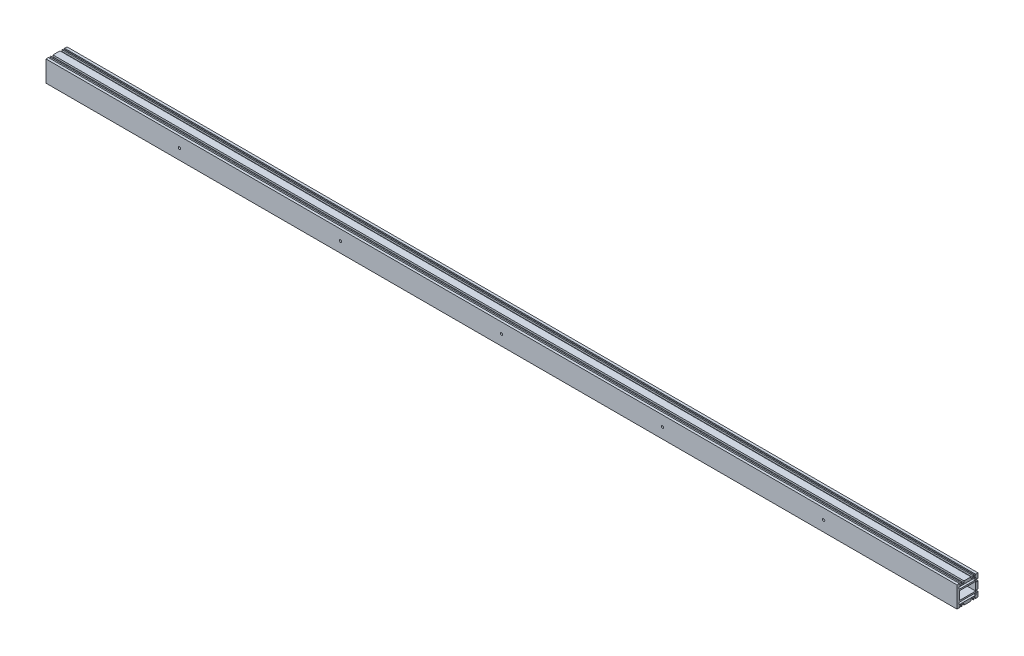
SolidWorks part; units mm, degrees
ref_plane "前视基准面" through (0, 0, 0) normal (0, 0, 1) x (1, 0, 0)
ref_plane "上视基准面" through (0, 0, 0) normal (0, 1, 0) x (1, 0, 0)
ref_plane "右视基准面" through (0, 0, 0) normal (1, 0, 0) x (0, 0, -1)
sketch "草图1" plane through (0, 0, 0) normal (1, 0, 0) x (0, 0, -1)
  line L0 (-15, 15) -> (15, -15) construction
  line L1 (-15, 15) -> (-11.5, 15)
  line L2 (-15, 15) -> (-15, -15)
  line L3 (-15, -15) -> (-11.5, -15)
  line L4 (15, 15) -> (15, 8)
  line L5 (15, 15) -> (-15, -15) construction
  line L6 (-11.5, 15) -> (-11.5, 13.5)
  line L7 (-11.5, 13.5) -> (-11, 13.5)
  line L8 (-11, 13.5) -> (-11, 12)
  line L9 (-11, 12) -> (-9.5, 12)
  line L10 (-9.5, 12) -> (-9.5, 15)
  line L11 (-9.5, 15) -> (-8, 15)
  line L12 (-8, 15) -> (-8, 12.5)
  line L13 (-8, 12.5) -> (-5, 12.5)
  line L14 (-5, 12.5) -> (-5, 15)
  line L15 (-5, 15) -> (5, 15)
  line L16 (0, 21.5201) -> (0, -18.309) construction
  line L17 (0, 55) -> (0, -55) construction
  line L18 (5, 12.5) -> (5, 15)
  line L19 (8, 12.5) -> (5, 12.5)
  line L20 (8, 15) -> (8, 12.5)
  line L21 (9.5, 15) -> (8, 15)
  line L22 (9.5, 12) -> (9.5, 15)
  line L23 (11, 12) -> (9.5, 12)
  line L24 (11, 13.5) -> (11, 12)
  line L25 (11.5, 13.5) -> (11, 13.5)
  line L26 (11.5, 15) -> (11.5, 13.5)
  line L27 (8, 15) -> (9.5, 15)
  line L28 (11.5, 15) -> (15, 15)
  line L29 (-19.8303, 0) -> (22.13, 0) construction
  line L30 (55, 0) -> (-55, 0) construction
  line L31 (8, -15) -> (9.5, -15)
  line L32 (11.5, -15) -> (11.5, -13.5)
  line L33 (11.5, -13.5) -> (11, -13.5)
  line L34 (11, -13.5) -> (11, -12)
  line L35 (11, -12) -> (9.5, -12)
  line L36 (9.5, -12) -> (9.5, -15)
  line L37 (9.5, -15) -> (8, -15)
  line L38 (8, -15) -> (8, -12.5)
  line L39 (8, -12.5) -> (5, -12.5)
  line L40 (5, -12.5) -> (5, -15)
  line L41 (-5, -15) -> (5, -15)
  line L42 (-5, -12.5) -> (-5, -15)
  line L43 (-8, -12.5) -> (-5, -12.5)
  line L44 (-8, -15) -> (-8, -12.5)
  line L45 (-9.5, -15) -> (-8, -15)
  line L46 (-9.5, -12) -> (-9.5, -15)
  line L47 (-11, -12) -> (-9.5, -12)
  line L48 (-11, -13.5) -> (-11, -12)
  line L49 (-11.5, -13.5) -> (-11, -13.5)
  line L50 (-11.5, -15) -> (-11.5, -13.5)
  line L51 (-9.5, -15) -> (-8, -15)
  line L52 (-5, -15) -> (5, -15)
  line L53 (8, -15) -> (9.5, -15)
  line L54 (11.5, -15) -> (15, -15)
  line L55 (15, 8) -> (12.5, 8)
  line L56 (12.5, 8) -> (12.5, 5)
  line L57 (12.5, 5) -> (15, 5)
  line L58 (12.5, -5) -> (15, -5)
  line L59 (12.5, -8) -> (12.5, -5)
  line L60 (15, -8) -> (12.5, -8)
  line L61 (15, 5) -> (15, -5)
  line L62 (15, -8) -> (15, -15)
  line L63 (12, -10.5) -> (12, -8.5)
  line L64 (-11.5, 11) -> (11.5, 11)
  line L65 (-12, 10.5) -> (-12, 8.5)
  line L66 (-11.5, 8) -> (11.5, 8)
  line L67 (12, 10.5) -> (12, 8.5)
  line L68 (-11.5, -8) -> (11.5, -8)
  line L69 (-12, -10.5) -> (-12, -8.5)
  line L70 (-11.5, -11) -> (11.5, -11)
  line L72 (-11.75, 6) -> (11.75, 6)
  line L73 (-11.75, 6) -> (-11.75, -6)
  line L74 (-11.75, -6) -> (11.75, -6)
  line L75 (11.75, 6) -> (11.75, -6)
  arc A0 (12, 8.5) -> (11.5, 8) centre (11.5, 8.5) cw
  arc A1 (11.5, 11) -> (12, 10.5) centre (11.5, 10.5) cw
  arc A2 (-11.5, 11) -> (-12, 10.5) centre (-11.5, 10.5) ccw
  arc A3 (-11.5, 8) -> (-12, 8.5) centre (-11.5, 8.5) cw
  arc A8 (-11.5, -8) -> (-12, -8.5) centre (-11.5, -8.5) ccw
  arc A9 (-11.5, -11) -> (-12, -10.5) centre (-11.5, -10.5) cw
  arc A10 (11.5, -11) -> (12, -10.5) centre (11.5, -10.5) ccw
  arc A11 (12, -8.5) -> (11.5, -8) centre (11.5, -8.5) ccw
  point P69 (12, 11)
  point P72 (-12, 11)
  point P77 (-11, -13.5)
  point P80 (11, -13.5)
  point P83 (11, 13.5)
  point P86 (-11, 13.5)
  point P99 (-12, -11)
  point P100 (12, -11)
  dimension "D17" = 0.5
  dimension "D1" = 3.5
  dimension "D2" = 1.5
  dimension "D3" = 0.5
  dimension "D4" = 1.5
  dimension "D5" = 3
  dimension "D6" = 30
  dimension "D7" = 30
  dimension "D8" = 1.5
  dimension "D9" = 2.5
  dimension "D10" = 3
  dimension "D11" = 2.5
  dimension "D12" = 7
  dimension "D13" = 3
  dimension "D14" = 4
  dimension "D15" = 3
  dimension "D16" = 24
  dimension "D19" = 23.5
  dimension "D20" = 12
extrude "凸台-拉伸1" add sketch "草图1" along normal mid plane 1301
hole_wizard "M6 螺纹孔1" positions "草图3" profile "草图2" tap size "M6" standard "GB"
sketch "草图3" plane through (0, 0, -15) normal (0, 0, -1) x (-1, 0, 0)
  point P0 (-630.5, 0)
  point P3 (-615.5, 0)
  point P6 (342.5, 0)
  point P9 (327.5, 0)
  point P12 (427.5, 0)
  point P15 (412.5, 0)
  point P18 (630.5, 0)
  point P21 (615.5, 0)
sketch "草图2" plane through (630.5, 0, -15) normal (1, 0, 0) x (0, 1, 0)
  line L0 (0, 0) -> (0, 20.5022)
  line L1 (0, 20.5022) -> (2.5, 19)
  line L2 (2.5, 19) -> (2.5, 0)
  line L5 (2.5, 0) -> (0, 0)
  line L10 (0, 20.5022) -> (-2.5, 19) construction
  line L11 (0, -6.35) -> (0, 107.95) construction
  dimension "螺纹孔钻头直径" = 5
  dimension "螺纹孔钻头深度" = 19
  dimension "导头角度" = 118
cosmetic thread "孔螺蚊线1" parameters "D1"=3.25, "D2"=6
cosmetic thread "孔螺蚊线2" parameters "D1"=3.25, "D2"=6
cosmetic thread "孔螺蚊线3" parameters "D1"=3.25, "D2"=6
cosmetic thread "孔螺蚊线4" parameters "D1"=3.25, "D2"=6
cosmetic thread "孔螺蚊线7" parameters "D1"=3.25, "D2"=6
cosmetic thread "孔螺蚊线8" parameters "D1"=3.25, "D2"=6
cosmetic thread "孔螺蚊线9" parameters "D1"=3.25, "D2"=6
cosmetic thread "孔螺蚊线10" parameters "D1"=3.25, "D2"=6
hole_wizard "M4 螺纹孔1" positions "草图5" profile "草图4" tap size "M4" standard "GB"
sketch "草图5" plane through (0, 0, 15) normal (0, 0, 1) x (1, 0, 0)
  line L0 (650.5, -15) -> (-650.5, -15) construction
  line L1 (650.5, 15) -> (650.5, -15) construction
  line L2 (-650.5, 15) -> (-650.5, -15) construction
  point P0 (-460, 0)
  point P2 (-230, 0)
  point P4 (0, 0)
  point P7 (230, 0)
  point P9 (460, 0)
  dimension "D1" = 15
  dimension "D2" = 190.5
  dimension "D3" = 420.5
  dimension "D4" = 15
  dimension "D5" = 15
  dimension "D6" = 190.5
  dimension "D7" = 420.5
  dimension "D8" = 15
sketch "草图4" plane through (-460, 0, 15) normal (1, 0, 0) x (0, -1, 0)
  line L0 (0, 0) -> (0, 16.4914)
  line L1 (0, 16.4914) -> (1.65, 15.5)
  line L2 (1.65, 15.5) -> (1.65, 0)
  line L5 (1.65, 0) -> (0, 0)
  line L10 (0, 16.4914) -> (-1.65, 15.5) construction
  line L11 (0, -6.35) -> (0, 107.95) construction
  dimension "螺纹孔钻头直径" = 3.3
  dimension "螺纹孔钻头深度" = 15.5
  dimension "导头角度" = 118
cosmetic thread "孔螺蚊线11" parameters "D1"=3.25, "D2"=4
cosmetic thread "孔螺蚊线12" parameters "D1"=3.25, "D2"=4
cosmetic thread "孔螺蚊线13" parameters "D1"=3.25, "D2"=4
cosmetic thread "孔螺蚊线14" parameters "D1"=3.25, "D2"=4
cosmetic thread "孔螺蚊线15" parameters "D1"=3.25, "D2"=4
hole_wizard "M6 螺纹孔2" positions "草图7" profile "草图6" tap size "M6" standard "GB"
sketch "草图7" plane through (0, -15, 0) normal (0, -1, 0) x (-1, 0, 0)
  line L0 (-650.5, 15) -> (650.5, 15) construction
  line L1 (-650.5, -5) -> (-650.5, 5) construction
  line L3 (650.5, -5) -> (650.5, 5) construction
  point P0 (310.5, 0)
  point P2 (285.5, 0)
  point P4 (-285.5, 0)
  point P6 (-310.5, 0)
  point P8 (590.5, 0)
  point P10 (470.5, 0)
  dimension "D1" = 15
  dimension "D2" = 15
  dimension "D3" = 15
  dimension "D4" = 15
  dimension "D5" = 180
  dimension "D6" = 60
  dimension "D7" = 340
  dimension "D8" = 365
  dimension "D9" = 15
  dimension "D10" = 15
  dimension "D11" = 340
  dimension "D12" = 365
sketch "草图6" plane through (-310.5, -15, 0) normal (1, 0, 0) x (0, 0, -1)
  line L0 (0, 0) -> (0, 18.5022)
  line L1 (0, 18.5022) -> (2.5, 17)
  line L2 (2.5, 17) -> (2.5, 0)
  line L5 (2.5, 0) -> (0, 0)
  line L10 (0, 18.5022) -> (-2.5, 17) construction
  line L11 (0, -6.35) -> (0, 107.95) construction
  dimension "螺纹孔钻头直径" = 5
  dimension "螺纹孔钻头深度" = 17
  dimension "导头角度" = 118
cosmetic thread "孔螺蚊线16" parameters "D1"=9, "D2"=6
cosmetic thread "孔螺蚊线17" parameters "D1"=9, "D2"=6
cosmetic thread "孔螺蚊线18" parameters "D1"=9, "D2"=6
cosmetic thread "孔螺蚊线19" parameters "D1"=9, "D2"=6
cosmetic thread "孔螺蚊线20" parameters "D1"=9, "D2"=6
cosmetic thread "孔螺蚊线21" parameters "D1"=9, "D2"=6
hole_wizard "M4 螺纹孔2" positions "草图9" profile "草图8" tap size "M4" standard "GB"
sketch "草图9" plane through (0, -15, 0) normal (0, -1, 0) x (-1, 0, 0)
  line L0 (-650.5, 15) -> (650.5, 15) construction
  line L2 (650.5, -5) -> (650.5, 5) construction
  point P0 (642.5, 0)
  point P2 (615.5, 0)
  dimension "D1" = 15
  dimension "D2" = 15
  dimension "D3" = 8
  dimension "D4" = 35
sketch "草图8" plane through (-642.5, -15, 0) normal (1, 0, 0) x (0, 0, -1)
  line L0 (0, 0) -> (0, 12.4914)
  line L1 (0, 12.4914) -> (1.65, 11.5)
  line L2 (1.65, 11.5) -> (1.65, 0)
  line L5 (1.65, 0) -> (0, 0)
  line L10 (0, 12.4914) -> (-1.65, 11.5) construction
  line L11 (0, -6.35) -> (0, 107.95) construction
  dimension "螺纹孔钻头直径" = 3.3
  dimension "螺纹孔钻头深度" = 11.5
  dimension "导头角度" = 118
cosmetic thread "孔螺蚊线22" parameters "D1"=8, "D2"=4
cosmetic thread "孔螺蚊线23" parameters "D1"=8, "D2"=4
